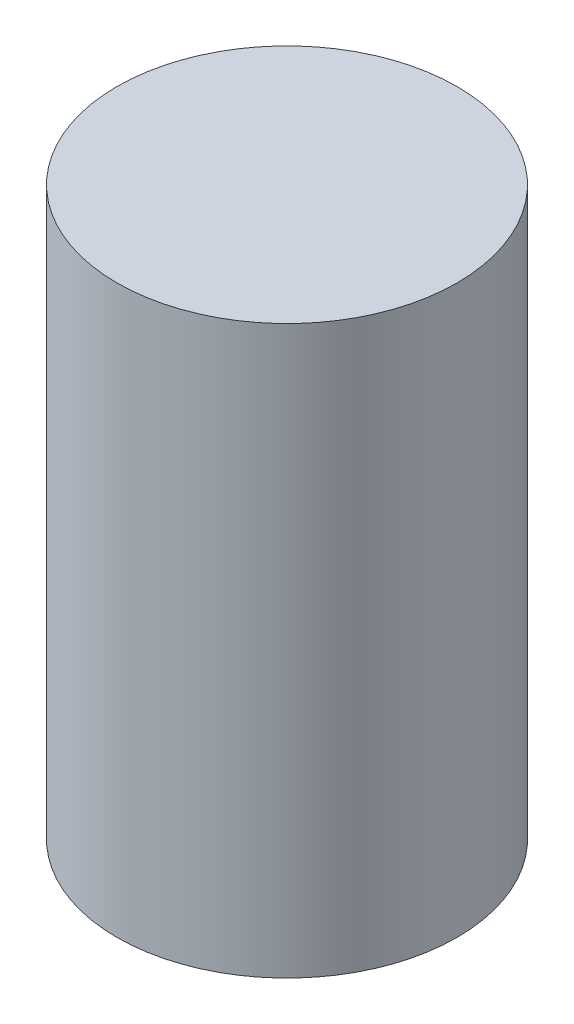
SolidWorks part; units mm, degrees
ref_plane "Front Plane" through (0, 0, 0) normal (0, 0, 1) x (1, 0, 0)
ref_plane "Top Plane" through (0, 0, 0) normal (0, 1, 0) x (1, 0, 0)
ref_plane "Right Plane" through (0, 0, 0) normal (1, 0, 0) x (0, 0, -1)
sketch "Sketch1" plane through (0, 0, 0) normal (0, 1, 0) x (1, 0, 0)
  circle A0 centre (0, 0) radius 60
  dimension "D1" = 120
extrude "Boss-Extrude1" add sketch "Sketch1" along normal blind 200
